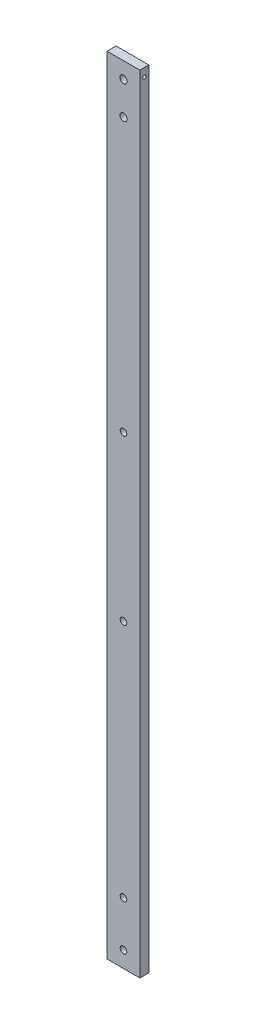
SolidWorks part; units mm, degrees
material "6061-T6 (SS)"
ref_plane "Front Plane" through (0, 0, 0) normal (0, 0, 1) x (1, 0, 0)
ref_plane "Top Plane" through (0, 0, 0) normal (0, 1, 0) x (1, 0, 0)
ref_plane "Right Plane" through (0, 0, 0) normal (1, 0, 0) x (0, 0, -1)
sketch "Sketch1" plane through (0, 0, 0) normal (0, 0, 1) x (1, 0, 0)
  line L0 (0, 304.8) -> (0, -304.8) construction
  line L1 (-12.7, -304.8) -> (12.7, -304.8)
  line L2 (-12.7, -304.8) -> (-12.7, 304.8)
  line L3 (-12.7, 304.8) -> (12.7, 304.8)
  line L4 (12.7, -304.8) -> (12.7, 304.8)
  line L5 (-12.7, -304.8) -> (12.7, 304.8) construction
  line L6 (-12.7, 304.8) -> (12.7, -304.8) construction
  circle A1 centre (0, -257.3) radius 2.5527
  circle A2 centre (0, -292.3) radius 2.5527
  circle A3 centre (0, 292.3) radius 2.794
  circle A4 centre (0, 266.9) radius 2.794
  point P0 (0, 0)
  dimension "D3" = 35
  dimension "D4" = 12.5
  dimension "D5" = 5.1054
  dimension "D6" = 12.5
  dimension "D7" = 5.1054
  dimension "D8" = 5.588
  dimension "D9" = 5.588
  dimension "D10" = 25.4
  dimension "D1" = 25.4
  dimension "D2" = 609.6
extrude "Boss-Extrude1" add sketch "Sketch1" along normal blind 7
sketch "Sketch2" plane through (12.7, 0, 0) normal (1, 0, 0) x (0, 0, -1)
  line L0 (-7, 304.8) -> (0, 304.8) construction
  circle A0 centre (-3.5, 298.45) radius 1.3334
  dimension "D1" = 6.35
extrude "Cut-Extrude1" cut sketch "Sketch2" against normal through all
sketch "Sketch3" plane through (0, 0, 0) normal (0, 0, -1) x (-1, 0, 0)
  line L0 (0, 304.8) -> (0, -304.8) construction
  line L1 (-12.7, 304.8) -> (12.7, 304.8) construction
  line L2 (12.7, -304.8) -> (-12.7, -304.8) construction
  line L3 (0, -257.3) -> (0, -292.3) construction
  line L4 (-997.4993, -274.8) -> (49002.5007, -274.8) construction
  circle A1 centre (0, -71.6) radius 2.5527
  circle A2 centre (0, 55.4) radius 2.5527
  circle A4 centre (0, -292.3) radius 2.5527 construction
  circle A5 centre (0, -257.3) radius 2.5527 construction
  dimension "D1" = 203.2
  dimension "D2" = 5.1054
  dimension "D3" = 127
extrude "Cut-Extrude2" cut sketch "Sketch3" against normal through all contours A2
